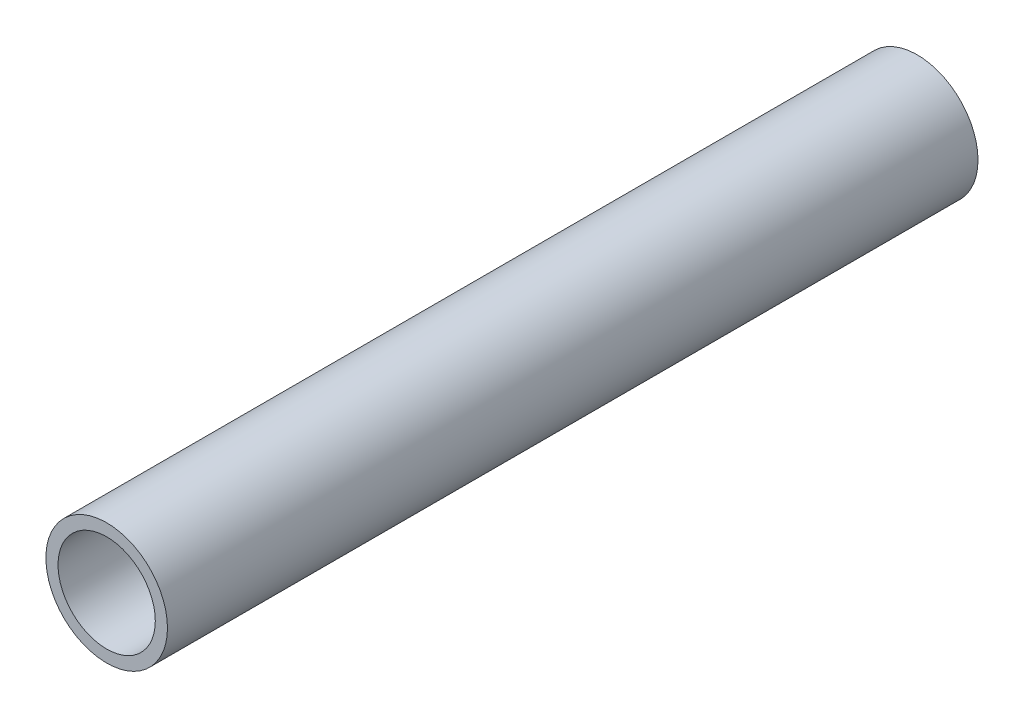
SolidWorks part; units mm, degrees
material "EM-CF"
ref_plane "Płaszczyzna przednia" through (0, 0, 0) normal (0, 0, 1) x (1, 0, 0)
ref_plane "Płaszczyzna górna" through (0, 0, 0) normal (0, 1, 0) x (1, 0, 0)
ref_plane "Płaszczyzna prawa" through (0, 0, 0) normal (1, 0, 0) x (0, 0, -1)
sketch "Szkic1" plane through (0, 0, 0) normal (0, 0, 1) x (1, 0, 0)
  circle A0 centre (0, 0) radius 12
  circle A1 centre (0, 0) radius 15
  dimension "D1" = 3
  dimension "D2" = 30
extrude "Dodanie-wyciągnięcie1" add sketch "Szkic1" along normal blind 200
